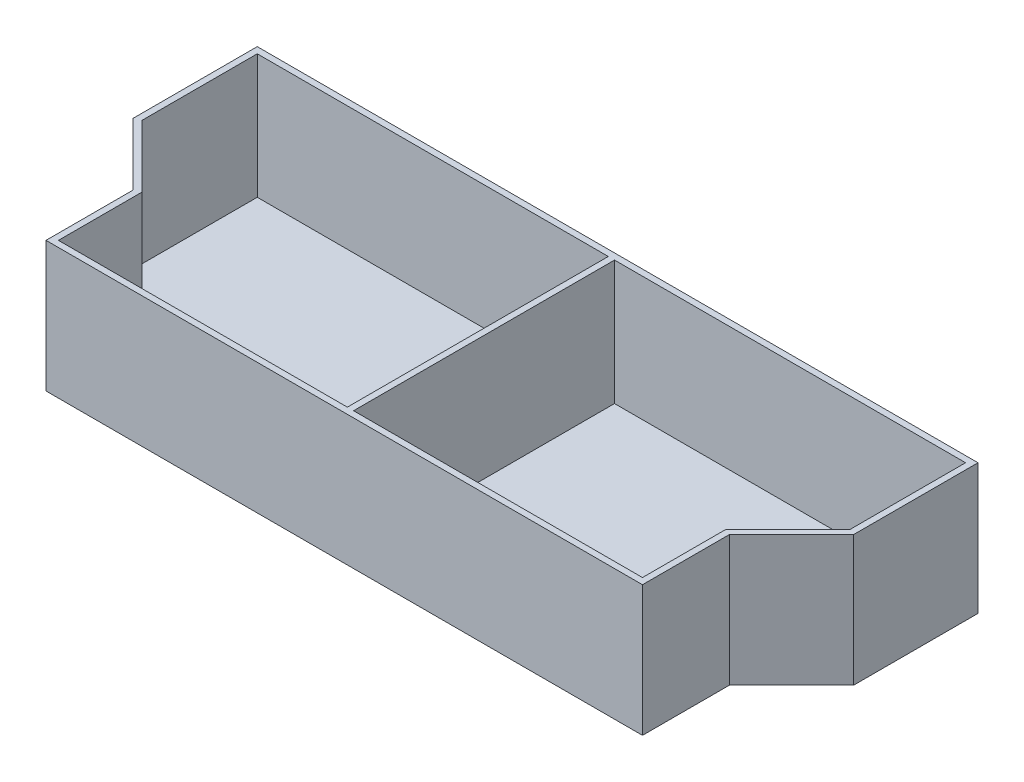
SolidWorks part; units mm, degrees
ref_plane "Front Plane" through (0, 0, 0) normal (0, 0, 1) x (1, 0, 0)
ref_plane "Top Plane" through (0, 0, 0) normal (0, 1, 0) x (1, 0, 0)
ref_plane "Right Plane" through (0, 0, 0) normal (1, 0, 0) x (0, 0, -1)
sketch "Sketch1" plane through (0, 0, 0) normal (0, 1, 0) x (1, 0, 0)
  line L0 (0, 0) -> (-609.6, 0)
  line L1 (-609.6, 0) -> (-609.6, 177.8)
  line L2 (-609.6, 177.8) -> (-736.6, 304.8)
  line L3 (-736.6, 304.8) -> (-736.6, 558.8)
  line L4 (-736.6, 558.8) -> (736.6, 558.8)
  line L5 (736.6, 558.8) -> (736.6, 304.8)
  line L6 (736.6, 304.8) -> (609.6, 177.8)
  line L7 (609.6, 177.8) -> (609.6, 0)
  line L8 (609.6, 0) -> (0, 0)
  line L9 (-723.9, 310.0605) -> (-723.9, 546.1)
  line L10 (-723.9, 546.1) -> (723.9, 546.1)
  line L11 (723.9, 546.1) -> (723.9, 310.0605)
  line L12 (723.9, 310.0605) -> (596.9, 183.0605)
  line L13 (596.9, 183.0605) -> (596.9, 12.7)
  line L14 (596.9, 12.7) -> (0, 12.7)
  line L15 (0, 12.7) -> (-596.9, 12.7)
  line L16 (-596.9, 12.7) -> (-596.9, 183.0605)
  line L17 (-596.9, 183.0605) -> (-723.9, 310.0605)
  point P19 (-609.6, 0)
  dimension "D1" = 1473.2
  dimension "D2" = 558.8
  dimension "D3" = 177.8
  dimension "D4" = 135
  dimension "D5" = 1219.2
  dimension "D7" = 177.8
  dimension "D8" = 609.6
  dimension "D9" = 12.7
extrude "Boss-Extrude1" add sketch "Sketch1" along normal blind 254
sketch "Sketch2" plane through (0, 0, 0) normal (0, -1, 0) x (1, 0, 0)
  line L8 (609.6, -177.8) -> (609.6, 0)
  line L9 (609.6, 0) -> (-609.6, 0)
  line L10 (-609.6, 0) -> (-609.6, -177.8)
  line L11 (-609.6, -177.8) -> (-736.6, -304.8)
  line L12 (-736.6, -304.8) -> (-736.6, -558.8)
  line L13 (-736.6, -558.8) -> (736.6, -558.8)
  line L14 (736.6, -558.8) -> (736.6, -304.8)
  line L15 (736.6, -304.8) -> (609.6, -177.8)
  line L16 (609.6, -177.8) -> (609.6, 0)
  line L17 (609.6, 0) -> (-609.6, 0)
  line L18 (-609.6, 0) -> (-609.6, -177.8)
  line L19 (-609.6, -177.8) -> (-736.6, -304.8)
  line L20 (-736.6, -304.8) -> (-736.6, -558.8)
  line L21 (-736.6, -558.8) -> (736.6, -558.8)
  line L22 (736.6, -558.8) -> (736.6, -304.8)
  line L23 (736.6, -304.8) -> (609.6, -177.8)
  dimension "D1" = 0
extrude "Boss-Extrude2" add sketch "Sketch2" along normal blind 12.7
sketch "Sketch3" plane through (0, 0, 0) normal (0, 1, 0) x (1, 0, 0)
  line L0 (-6.35, 12.7) -> (-6.35, 546.1)
  line L1 (-6.35, 12.7) -> (6.35, 12.7)
  line L2 (-6.35, 546.1) -> (6.35, 546.1)
  line L3 (6.35, 12.7) -> (6.35, 546.1)
  line L4 (-6.35, 12.7) -> (6.35, 546.1) construction
  line L5 (-6.35, 546.1) -> (6.35, 12.7) construction
  line L6 (-596.9, 12.7) -> (596.9, 12.7) construction
  point P0 (17.0782, 12.7)
  point P1 (0, 279.4)
  dimension "D1" = 12.7
  dimension "D2" = 533.4
  dimension "D3" = 0
extrude "Boss-Extrude3" add sketch "Sketch3" along normal up to surface (254 mm away) up to face at (0, 254, -260.35)
